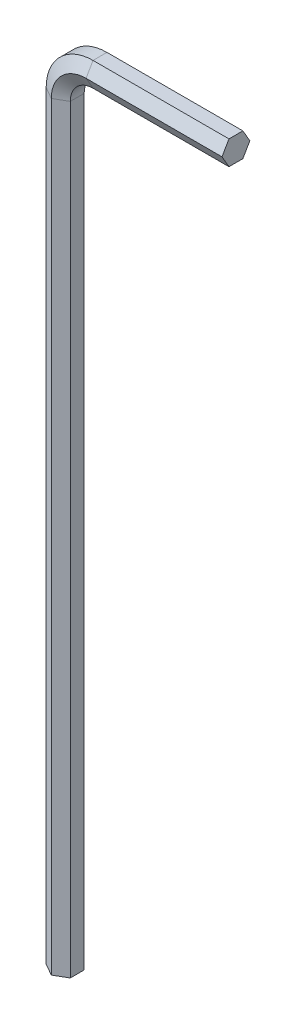
SolidWorks part; units mm, degrees
other "Defeature"
material "Plain Carbon Steel"
ref_plane "Front Plane" through (0, 0, 0) normal (0, 0, 1) x (1, 0, 0)
ref_plane "Top Plane" through (0, 0, 0) normal (0, 1, 0) x (1, 0, 0)
ref_plane "Right Plane" through (0, 0, 0) normal (1, 0, 0) x (0, 0, -1)
sketch "Sketch1" plane through (0, 0, 0) normal (0, 0, 1) x (1, 0, 0)
  line L0 (0, 0) -> (0, 87.2157)
  line L1 (4, 91.2157) -> (19.6157, 91.2157)
  arc A0 (0, 87.2157) -> (4, 91.2157) centre (4, 87.2157) cw
  point P8 (0, 91.2157)
  dimension "D4" = 4
  dimension "D2" = 91.2157
  dimension "D3" = 19.6157
sketch "Sketch2" plane through (0, 0, 0) normal (0, 1, 0) x (1, 0, 0)
  line L1 (0, 1.5985) -> (-1.3843, 0.7992)
  line L2 (-1.3843, 0.7992) -> (-1.3843, -0.7992)
  line L3 (-1.3843, -0.7992) -> (0, -1.5985)
  line L4 (0, -1.5985) -> (1.3843, -0.7992)
  line L5 (1.3843, -0.7992) -> (1.3843, 0.7992)
  line L6 (1.3843, 0.7992) -> (0, 1.5985)
  circle A0 centre (0, 0) radius 1.3843 construction
  dimension "D1" = 2.7686
sweep "Sweep1" add profiles "Sketch2" path "Sketch1"
